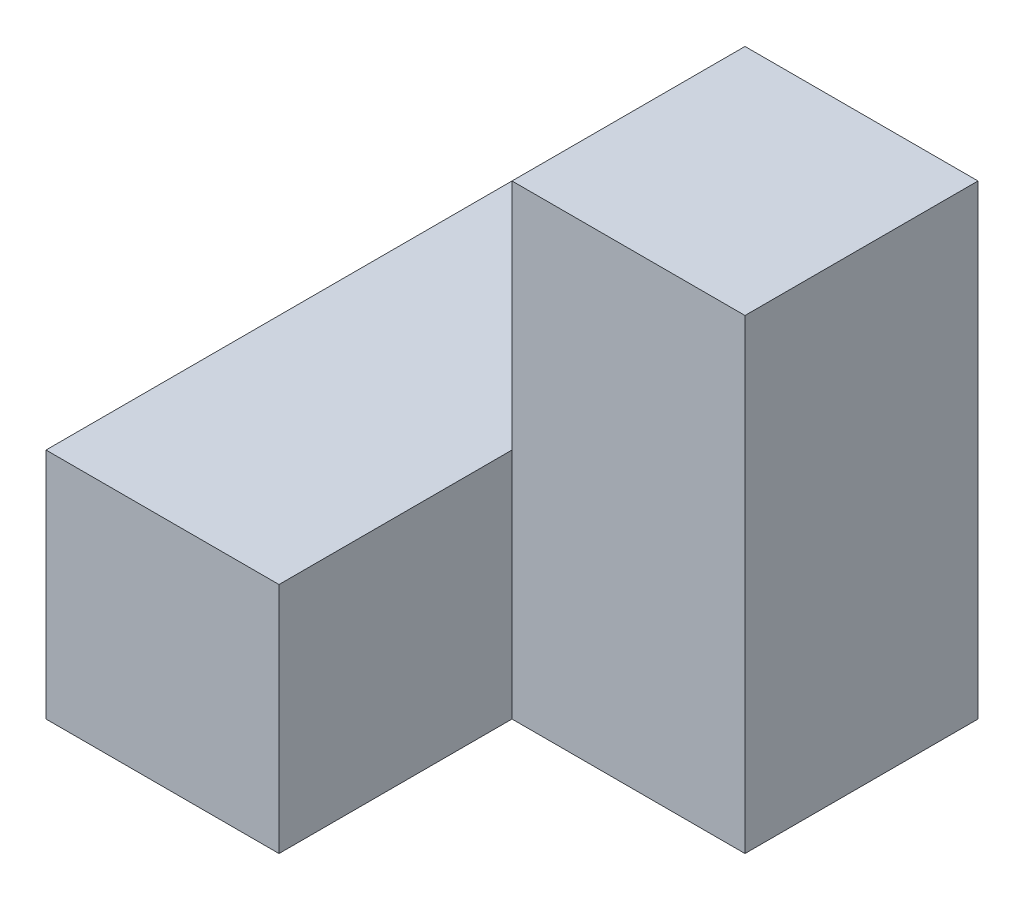
SolidWorks part; units mm, degrees
ref_plane "Front Plane" through (0, 0, 0) normal (0, 0, 1) x (1, 0, 0)
ref_plane "Top Plane" through (0, 0, 0) normal (0, 1, 0) x (1, 0, 0)
ref_plane "Right Plane" through (0, 0, 0) normal (1, 0, 0) x (0, 0, -1)
other "Center of Mass"
sketch "Sketch1" plane through (0, 0, 0) normal (0, 1, 0) x (1, 0, 0)
  line L0 (0, 0) -> (30, 0)
  line L1 (30, 0) -> (30, 30)
  line L2 (30, 30) -> (-30, 30)
  line L3 (-30, 30) -> (-30, -30)
  line L4 (-30, -30) -> (0, -30)
  line L5 (0, -30) -> (0, 0)
  dimension "D1" = 30
  dimension "D2" = 60
  dimension "D3" = 30
  dimension "D4" = 30
extrude "Boss-Extrude1" add sketch "Sketch1" along normal blind 30
sketch "Sketch2" plane through (0, 30, 0) normal (0, 1, 0) x (1, 0, 0)
  line L0 (30, 30) -> (-30, 30) construction
  line L1 (30, 0) -> (0, 0)
  line L2 (30, 0) -> (30, 30)
  line L3 (30, 30) -> (0, 30)
  line L4 (0, 0) -> (0, 30)
extrude "Boss-Extrude2" add sketch "Sketch2" along normal blind 30
